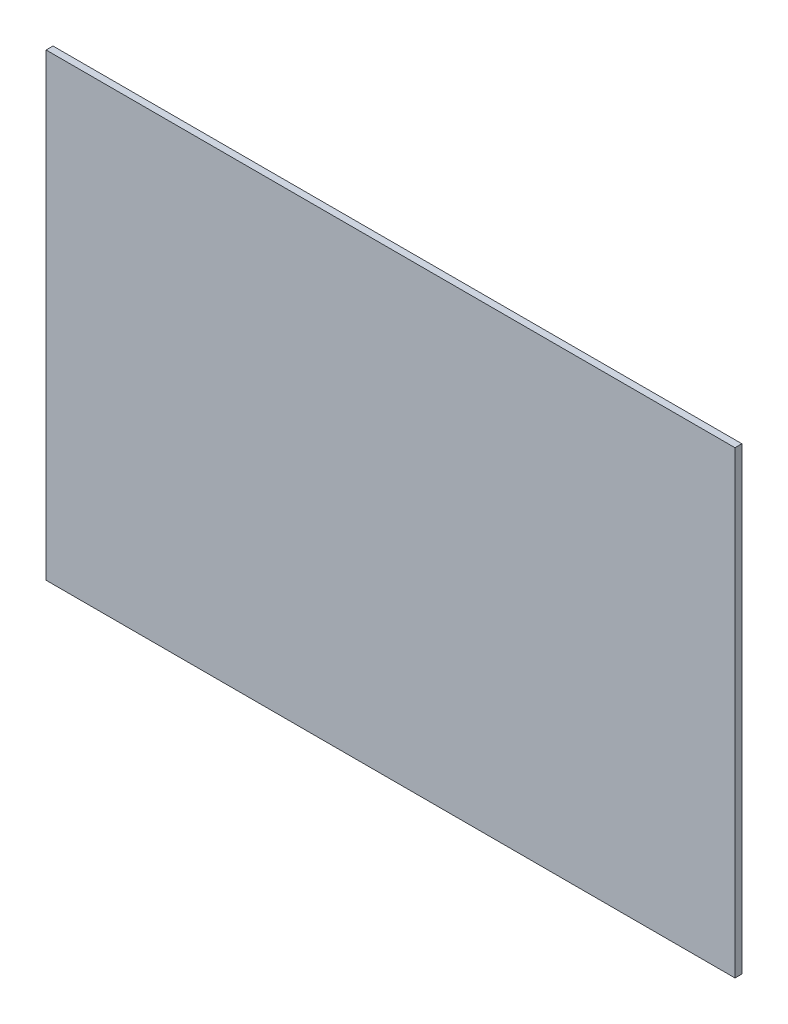
SolidWorks part; units mm, degrees
material "Balsa"
ref_plane "Front Plane" through (0, 0, 0) normal (0, 0, 1) x (1, 0, 0)
ref_plane "Top Plane" through (0, 0, 0) normal (0, 1, 0) x (1, 0, 0)
ref_plane "Right Plane" through (0, 0, 0) normal (1, 0, 0) x (0, 0, -1)
sketch "Sketch1" plane through (0, 0, 0) normal (0, 0, 1) x (1, 0, 0)
  line L1 (-773.5781, 479.8387) -> (726.4219, 479.8387)
  line L2 (-773.5781, 479.8387) -> (-773.5781, -520.1613)
  line L3 (-773.5781, -520.1613) -> (726.4219, -520.1613)
  line L4 (726.4219, 479.8387) -> (726.4219, -520.1613)
  line L5 (-773.5781, 479.8387) -> (726.4219, -520.1613) construction
  line L6 (-773.5781, -520.1613) -> (726.4219, 479.8387) construction
  point P0 (-23.5781, -20.1613)
  dimension "D1" = 1500
  dimension "D2" = 1000
extrude "Boss-Extrude1" add sketch "Sketch1" along normal blind 15
